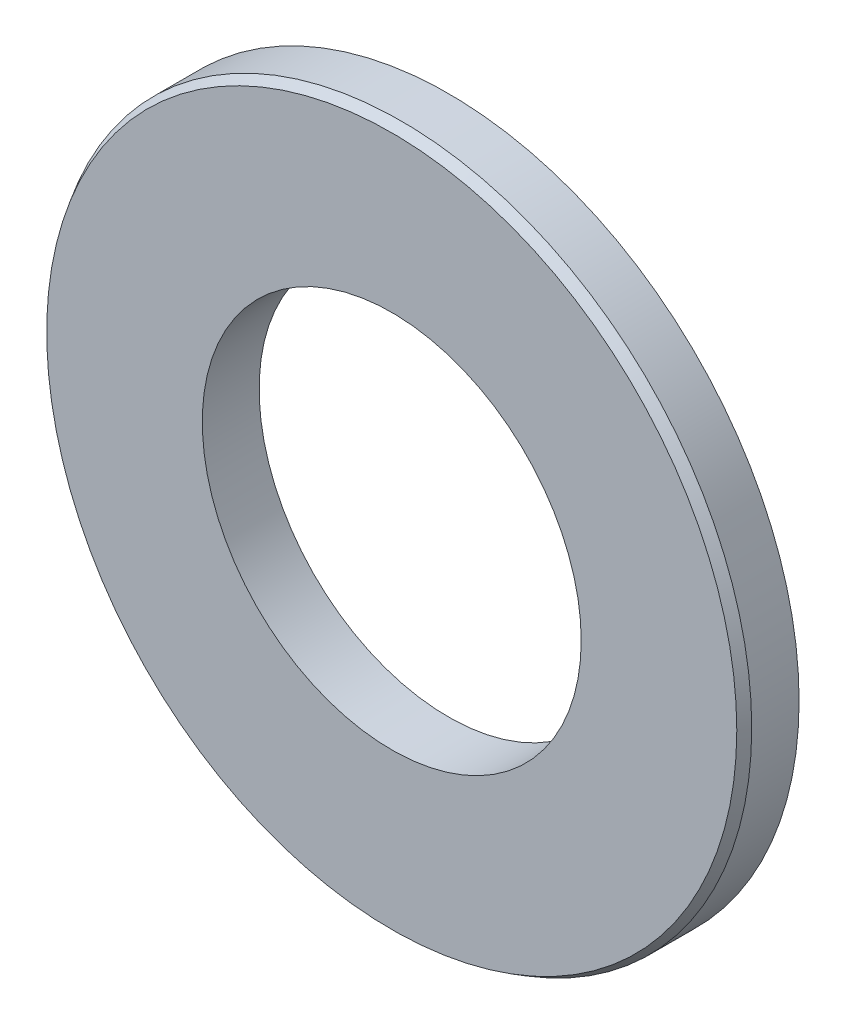
SolidWorks part; units mm, degrees
material "普通碳钢"
ref_plane "前视基准面" through (0, 0, 0) normal (0, 0, 1) x (1, 0, 0)
ref_plane "上视基准面" through (0, 0, 0) normal (0, 1, 0) x (1, 0, 0)
ref_plane "右视基准面" through (0, 0, 0) normal (1, 0, 0) x (0, 0, -1)
sketch "草图1" plane through (0, 0, 0) normal (0, 0, 1) x (1, 0, 0)
  line L0 (0, -27.9305) -> (0, 26.1225) construction
  line L1 (-29.6691, 0) -> (30.2697, 0) construction
  circle A0 centre (0, 0) radius 18.5
extrude "拉伸2" add sketch "草图1" along normal blind 3
sketch "草图2" plane through (0, 0, 3) normal (0, 0, 1) x (1, 0, 0)
  circle A0 centre (0, 0) radius 10
extrude "切除-拉伸1" cut sketch "草图2" against normal through all
chamfer "倒角1" distance 0.5 angle 30 1 edges at (18.5, 0, 3)
